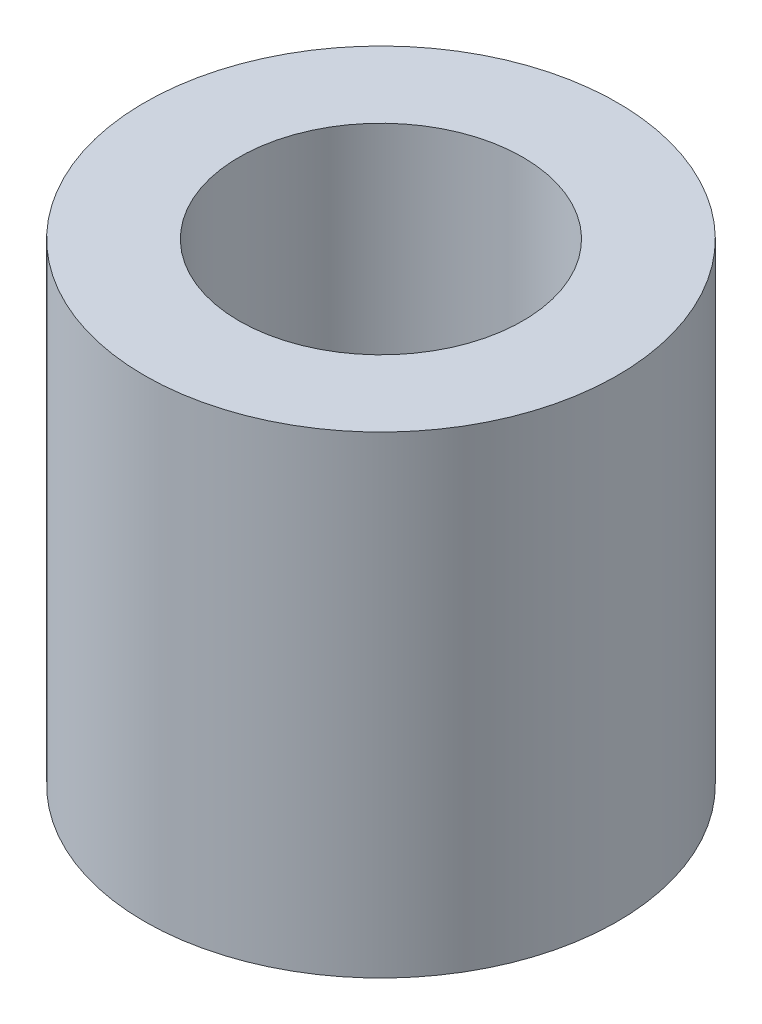
SolidWorks part; units mm, degrees
ref_plane "前视基准面" through (0, 0, 0) normal (0, 0, 1) x (1, 0, 0)
ref_plane "上视基准面" through (0, 0, 0) normal (0, 1, 0) x (1, 0, 0)
ref_plane "右视基准面" through (0, 0, 0) normal (1, 0, 0) x (0, 0, -1)
sketch "草图1" plane through (0, 0, 0) normal (0, 1, 0) x (1, 0, 0)
  circle A0 centre (0, 0) radius 3
  circle A1 centre (0, 0) radius 5
  dimension "D1" = 10
  dimension "D2" = 6
extrude "凸台-拉伸1" add sketch "草图1" along normal blind 10
